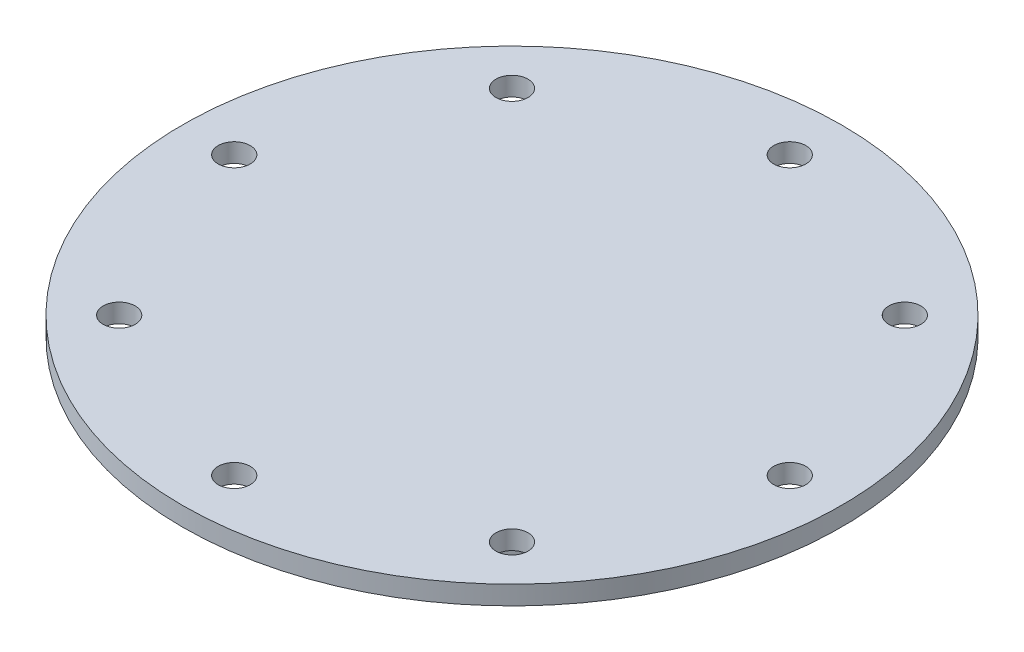
SolidWorks part; units mm, degrees
material "AISI 304"
ref_plane "Спереди" through (0, 0, 0) normal (0, 0, 1) x (1, 0, 0)
ref_plane "Сверху" through (0, 0, 0) normal (0, 1, 0) x (1, 0, 0)
ref_plane "Справа" through (0, 0, 0) normal (1, 0, 0) x (0, 0, -1)
sketch "Эскиз1" plane through (0, 0, 0) normal (0, 1, 0) x (1, 0, 0)
  line L0 (0, 0) -> (59, 0) construction
  circle A0 centre (0, 0) radius 70
  circle A1 centre (0, 0) radius 59 construction
  circle A2 centre (59, 0) radius 3.4
  circle A3 centre (41.7193, -41.7193) radius 3.4
  circle A4 centre (0, -59) radius 3.4
  circle A5 centre (-41.7193, -41.7193) radius 3.4
  circle A6 centre (-59, 0) radius 3.4
  circle A7 centre (-41.7193, 41.7193) radius 3.4
  circle A8 centre (0, 59) radius 3.4
  circle A9 centre (41.7193, 41.7193) radius 3.4
  dimension "D1" = 140
  dimension "D2" = 118
  dimension "D3" = 6.8
  dimension "D4" = 8
extrude "Бобышка-Вытянуть1" add sketch "Эскиз1" along normal blind 4
sketch "Эскиз2" plane through (0, 0, 0) normal (0, 1, 0) x (1, 0, 0)
  circle A0 centre (0, 0) radius 35
  circle A1 centre (0, 0) radius 40
  dimension "D1" = 80
  dimension "D2" = 70
extrude "Бобышка-Вытянуть2" add sketch "Эскиз2" against normal blind 21
fillet "Скругление2" radius 1 2 edges at (0, 0, 40) (0, 0, 35)
equation "\"Диаметр крышки нижней обоймы\"= 140мм"
equation "\"Толщина крышки нижней обоймы\"= 4мм"
equation "\"D1@Эскиз1\"=\"Диаметр крышки нижней обоймы\""
equation "\"D1@Бобышка-Вытянуть1\"=\"Толщина крышки нижней обоймы\""
